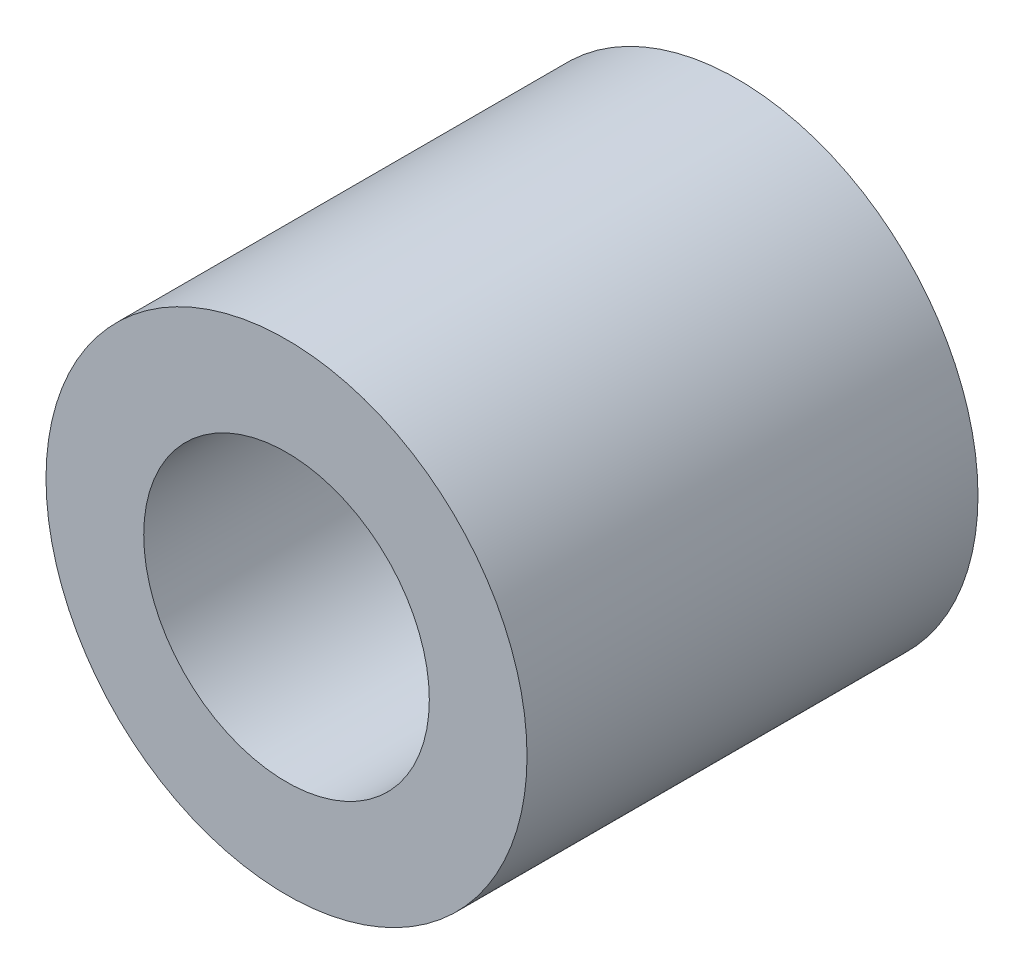
SolidWorks part; units mm, degrees
ref_plane "Plan de face" through (0, 0, 0) normal (0, 0, 1) x (1, 0, 0)
ref_plane "Plan de dessus" through (0, 0, 0) normal (0, 1, 0) x (1, 0, 0)
ref_plane "Plan de droite" through (0, 0, 0) normal (1, 0, 0) x (0, 0, -1)
sketch "Sketch1" plane through (0, 0, 0) normal (0, 0, 1) x (1, 0, 0)
  circle A0 centre (0, 0) radius 4.75
  circle A1 centre (0, 0) radius 8
  dimension "D1" = 16
  dimension "D2" = 9.5
extrude "Boss-Extrude1" add sketch "Sketch1" against normal blind 15
